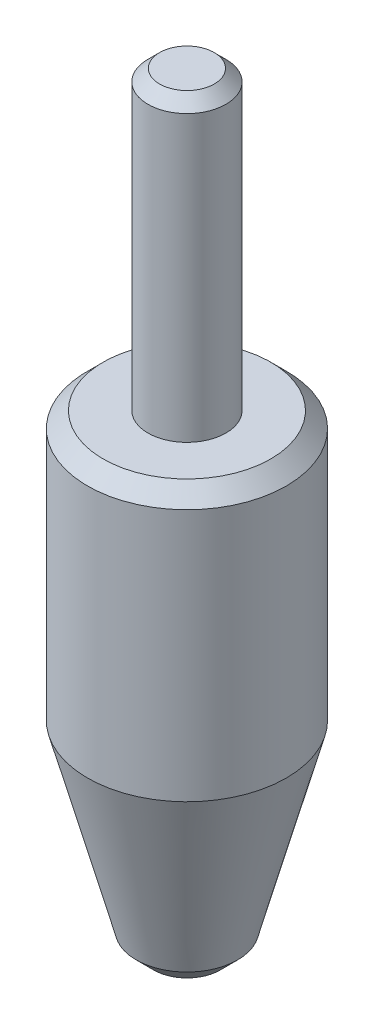
SolidWorks part; units mm, degrees
material "Cast Stainless Steel"
ref_plane "Plane1" through (0, 0, 0) normal (0, 0, 1) x (1, 0, 0)
ref_plane "Plane2" through (0, 0, 0) normal (0, 1, 0) x (1, 0, 0)
ref_plane "Plane3" through (0, 0, 0) normal (1, 0, 0) x (0, 0, -1)
sketch "Sketch1" plane through (0, 0, 0) normal (0, 0, 1) x (1, 0, 0)
  line L0 (0, -4.0768) -> (0, 10) construction
  line L1 (0, 10) -> (-0.5, 10)
  line L2 (-0.5, 10) -> (-0.5, 6.2)
  line L3 (-0.5, 6.2) -> (-1.275, 6.2)
  line L4 (-1.275, 6.2) -> (-1.275, 2.7575)
  line L5 (0, 10) -> (0, 0)
  line L6 (-0.425, 0.2) -> (-0.3464, 0.2)
  line L7 (-0.425, 0.2) -> (-0.65, 0.425)
  line L8 (-0.65, 0.425) -> (-1.275, 2.7575)
  arc A0 (-0.3464, 0.2) -> (0, 0) centre (0, 0.4) ccw
  dimension "D10" = 6.2
  dimension "D9" = 0.8
  dimension "D11" = 2.7575
  dimension "D1" = 15
  dimension "D2" = 1
  dimension "D3" = 3.8
  dimension "D4" = 2.55
  dimension "D5" = 45
  dimension "D6" = 0.2
  dimension "D7" = 0.85
  dimension "D8" = 1.3
revolve "Base-Revolve" add sketch "Sketch1"
chamfer "Chamfer1" distance 0.15 angle 45 1 edges at (0.5, 10, 0)
chamfer "Chamfer2" distance 0.2 angle 45 1 edges at (1.275, 6.2, 0)
ref_plane "Posição" through (0, 2.7575, 0) normal (0, 1, 0) x (-1, 0, 0)
